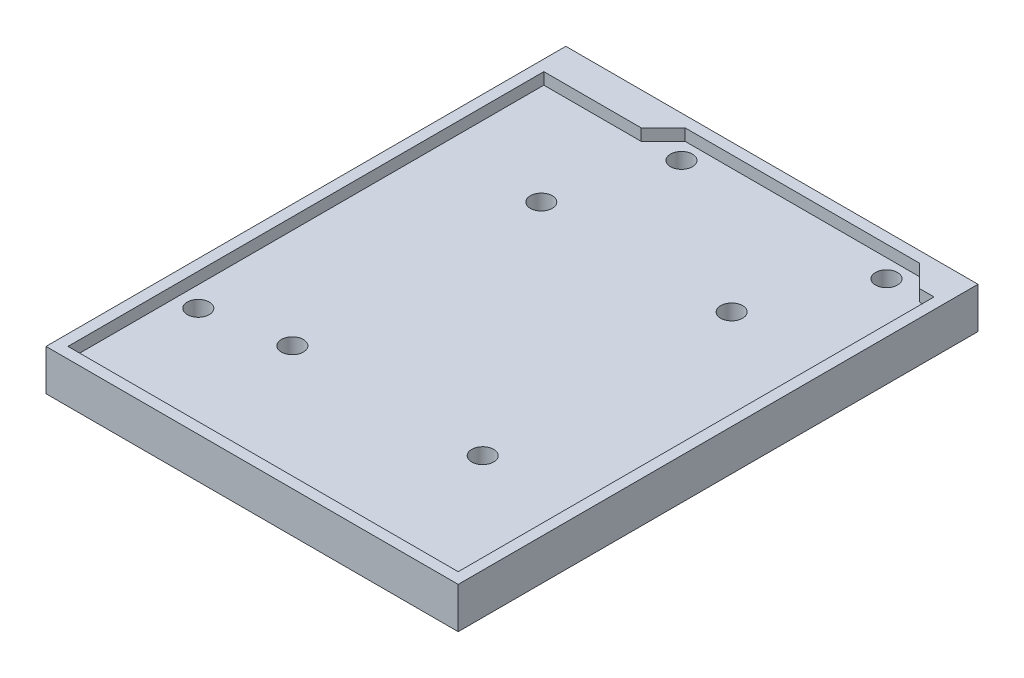
SolidWorks part; units mm, degrees
ref_plane "Front Plane" through (0, 0, 0) normal (0, 0, 1) x (1, 0, 0)
ref_plane "Top Plane" through (0, 0, 0) normal (0, 1, 0) x (1, 0, 0)
ref_plane "Right Plane" through (0, 0, 0) normal (1, 0, 0) x (0, 0, -1)
sketch "Sketch1" plane through (0, 0, 0) normal (0, 1, 0) x (1, 0, 0)
  line L1 (-28.15, 35.5) -> (28.15, 35.5)
  line L2 (-28.15, 35.5) -> (-28.15, -35.5)
  line L3 (-28.15, -35.5) -> (28.15, -35.5)
  line L4 (28.15, 35.5) -> (28.15, -35.5)
  line L5 (-28.15, 35.5) -> (28.15, -35.5) construction
  line L6 (-28.15, -35.5) -> (28.15, 35.5) construction
  point P0 (0, 0)
  dimension "D1" = 71
  dimension "D2" = 56.3
extrude "Boss-Extrude1" add sketch "Sketch1" along normal blind 5.6
sketch "Sketch2" plane through (0, 5.6, 0) normal (0, 1, 0) x (1, 0, 0)
  line L0 (-26.65, 35.5) -> (-26.65, -35.5) construction
  line L1 (28.15, 35.5) -> (-28.15, 35.5) construction
  line L2 (-28.15, -35.5) -> (28.15, -35.5) construction
  line L3 (-28.15, 35.5) -> (-28.15, -35.5) construction
  line L4 (26.65, 35.5) -> (26.65, -35.5) construction
  line L5 (28.15, -35.5) -> (28.15, 35.5) construction
  line L6 (-28.15, 34) -> (28.15, 34) construction
  line L7 (-28.15, -34) -> (28.15, -34) construction
  line L8 (26.65, -34) -> (-26.65, -34)
  line L9 (-26.65, -34) -> (-26.65, 31)
  line L10 (26.65, 31) -> (26.65, -34)
  line L11 (-26.65, 31) -> (-13.35, 31)
  line L12 (-10.35, 34) -> (21.65, 34)
  line L13 (-13.35, 31) -> (-10.35, 34)
  line L14 (26.65, 31) -> (24.65, 31)
  line L15 (21.65, 34) -> (24.65, 31)
  dimension "D1" = 1.5
  dimension "D2" = 1.5
  dimension "D3" = 1.5
  dimension "D4" = 1.5
  dimension "D5" = 65
  dimension "D6" = 13.3
  dimension "D7" = 68
  dimension "D8" = 32
  dimension "D9" = 3
  dimension "D10" = 2
extrude "Cut-Extrude1" cut sketch "Sketch2" against normal blind 1.6
sketch "Sketch3" plane through (0, 4, 0) normal (0, 1, 0) x (1, 0, 0)
  line L0 (26.65, -34) -> (26.65, 31) construction
  line L1 (-26.65, -34) -> (26.65, -34) construction
  line L2 (26.65, -34) -> (26.65, 31) construction
  circle A0 centre (-8.35, 31.5) radius 1.5
  circle A1 centre (19.65, 31.5) radius 1.5
  circle A2 centre (-23.85, -19) radius 1.5
  dimension "D1" = 35
  dimension "D3" = 28
  dimension "D4" = 50.5
  dimension "D2" = 65.5
  dimension "D5" = 15
extrude "Cut-Extrude2" cut sketch "Sketch3" against normal blind 4
sketch "Sketch5" plane through (0, 4, 0) normal (0, 1, 0) x (1, 0, 0)
  circle A0 centre (-13, 17) radius 1.5
  circle A1 centre (13, -17) radius 1.5
  circle A2 centre (13, 17) radius 1.5
  circle A3 centre (-13, -17) radius 1.5
  dimension "D1" = 13
  dimension "D3" = 13
  dimension "D2" = 17
  dimension "D4" = 17
extrude "Cut-Extrude3" cut sketch "Sketch5" against normal blind 4
